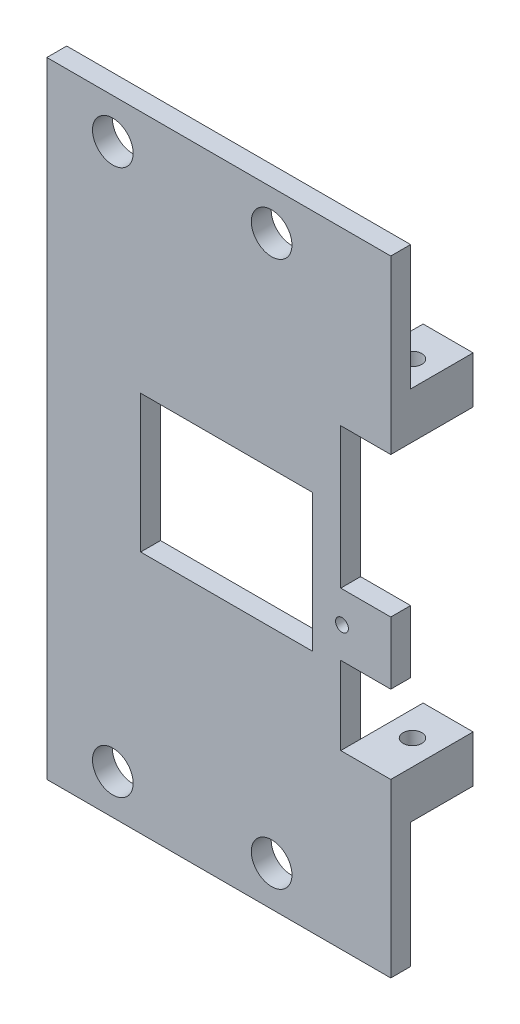
SolidWorks part; units mm, degrees
ref_plane "Front Plane" through (0, 0, 0) normal (0, 0, 1) x (1, 0, 0)
ref_plane "Top Plane" through (0, 0, 0) normal (0, 1, 0) x (1, 0, 0)
ref_plane "Right Plane" through (0, 0, 0) normal (1, 0, 0) x (0, 0, -1)
sketch "Sketch1" plane through (0, 0, 0) normal (0, 0, 1) x (1, 0, 0)
  line L1 (7.5, 12.5) -> (62.5, 12.5)
  line L2 (7.5, 12.5) -> (7.5, -87.5)
  line L3 (7.5, -87.5) -> (62.5, -87.5)
  line L4 (62.5, 12.5) -> (62.5, -87.5)
  line L5 (22.5, -26.5) -> (50, -26.5)
  line L6 (22.5, -26.5) -> (22.5, -48.5)
  line L7 (22.5, -48.5) -> (50, -48.5)
  line L8 (50, -26.5) -> (50, -48.5)
  line L9 (22.5, -26.5) -> (50, -48.5) construction
  line L10 (22.5, -48.5) -> (50, -26.5) construction
  point P5 (36.25, -37.5)
  dimension "D1" = 55
  dimension "D2" = 39
  dimension "D3" = 27.5
  dimension "D4" = 22
  dimension "D5" = 12.5
  dimension "D6" = 39
extrude "Boss-Extrude1" add sketch "Sketch1" along normal blind 3.175
sketch "Sketch2" plane through (0, 0, 0) normal (0, 0, -1) x (-1, 0, 0)
  line L1 (-62.5, -7.5) -> (-54.5, -7.5)
  line L2 (-62.5, -7.5) -> (-62.5, -67.5)
  line L3 (-62.5, -67.5) -> (-54.5, -67.5)
  line L4 (-54.5, -7.5) -> (-54.5, -67.5)
  line L5 (-7.5, -87.5) -> (-62.5, -87.5) construction
  line L6 (-62.5, 12.5) -> (-7.5, 12.5) construction
  dimension "D1" = 8
  dimension "D2" = 20
  dimension "D3" = 20
extrude "Boss-Extrude2" add sketch "Sketch2" along normal blind 10
sketch "Sketch3" plane through (0, 0, -10) normal (0, 0, -1) x (-1, 0, 0)
  line L0 (-62.5, -7.5) -> (-62.5, -67.5) construction
  line L1 (-62.5, -15) -> (-54.5, -15)
  line L2 (-62.5, -15) -> (-62.5, -60)
  line L3 (-62.5, -60) -> (-54.5, -60)
  line L4 (-54.5, -15) -> (-54.5, -60)
  line L5 (-54.5, -67.5) -> (-54.5, -7.5) construction
  line L6 (-62.5, -67.5) -> (-54.5, -67.5) construction
  line L7 (-54.5, -7.5) -> (-62.5, -7.5) construction
  dimension "D1" = 7.5
  dimension "D2" = 7.5
extrude "Cut-Extrude1" cut sketch "Sketch3" against normal blind 10
sketch "Sketch4" plane through (0, 12.5, 0) normal (0, 1, 0) x (1, 0, 0)
  line L0 (62.5, -3.175) -> (62.5, 0) construction
  line L1 (54.5, 10) -> (62.5, 10) construction
  circle A0 centre (58.5, 4.3) radius 1.5
  dimension "D1" = 3
  dimension "D2" = 4
  dimension "D3" = 5.7
extrude "Cut-Extrude2" cut sketch "Sketch4" against normal through all
sketch "Sketch5" plane through (0, 0, 0) normal (0, 0, -1) x (-1, 0, 0)
  line L0 (-7.5, -87.5) -> (-62.5, -87.5) construction
  line L1 (-62.5, -15) -> (-62.5, -60) construction
  line L2 (-62.5, 12.5) -> (-7.5, 12.5) construction
  circle A0 centre (-43.45, -81.125) radius 3.25
  circle A1 centre (-18.05, -81.125) radius 3.25
  circle A2 centre (-18.05, 6.125) radius 3.25
  circle A3 centre (-43.45, 6.125) radius 3.25
  dimension "D1" = 6.5
  dimension "D2" = 25.4
  dimension "D3" = 6.375
  dimension "D4" = 19.05
  dimension "D5" = 6.375
extrude "Cut-Extrude3" cut sketch "Sketch5" against normal through all
sketch "Sketch7" plane through (0, 0, 0) normal (0, 0, -1) x (-1, 0, 0)
  line L0 (-54.5, -15) -> (-62.5, -15) construction
  line L1 (-62.5, -60) -> (-54.5, -60)
  line L2 (-62.5, -60) -> (-62.5, -15)
  line L3 (-62.5, -15) -> (-54.5, -15)
  line L4 (-54.5, -60) -> (-54.5, -15)
  line L5 (-54.5, -67.5) -> (-54.5, -60) construction
extrude "Cut-Extrude5" cut sketch "Sketch7" against normal through all
sketch "Sketch8" plane through (54.5, 0, 0) normal (1, 0, 0) x (0, 0, -1)
  line L0 (-3.175, -60) -> (-3.175, -15) construction
  line L1 (0, -37.5) -> (-3.175, -37.5)
  line L2 (0, -37.5) -> (0, -47.5)
  line L3 (0, -47.5) -> (-3.175, -47.5)
  line L4 (-3.175, -37.5) -> (-3.175, -47.5)
  line L5 (0, -37.5) -> (-3.175, -47.5) construction
  line L6 (0, -47.5) -> (-3.175, -37.5) construction
  line L8 (-3.175, -60) -> (0, -60) construction
  point P0 (-1.5875, -42.5)
  dimension "D1" = 10
  dimension "D2" = 12.5
extrude "Boss-Extrude4" add sketch "Sketch8" along normal up to surface (8 mm away) up to face at (62.5, -71.6667, -2.275)
sketch "Sketch9" plane through (0, 0, 0) normal (0, 0, -1) x (-1, 0, 0)
  line L0 (-62.5, -37.5) -> (-62.5, -47.5) construction
  line L1 (-62.5, -47.5) -> (-54.5, -47.5) construction
  circle A0 centre (-54.7, -42.5) radius 1.025
  dimension "D2" = 2.05
  dimension "D1" = 7.8
  dimension "D3" = 5
extrude "Cut-Extrude6" cut sketch "Sketch9" against normal through all
